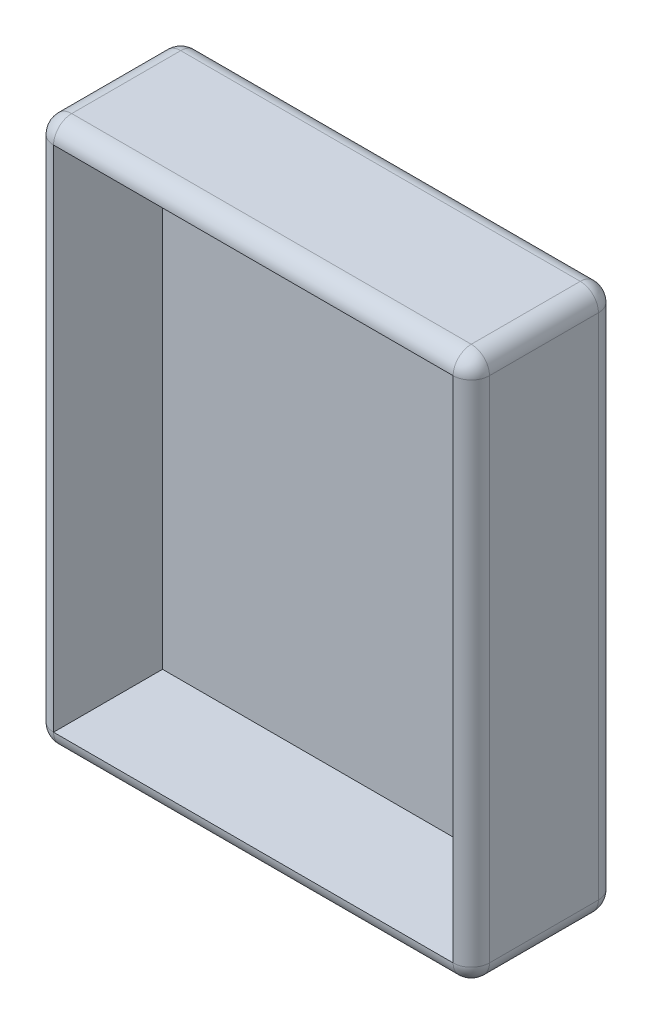
SolidWorks part; units mm, degrees
ref_plane "Front Plane" through (0, 0, 0) normal (0, 0, 1) x (1, 0, 0)
ref_plane "Top Plane" through (0, 0, 0) normal (0, 1, 0) x (1, 0, 0)
ref_plane "Right Plane" through (0, 0, 0) normal (1, 0, 0) x (0, 0, -1)
sketch "Sketch1" plane through (0, 0, 0) normal (0, 0, 1) x (1, 0, 0)
  line L1 (-87.9296, 121.1643) -> (32.0704, 121.1643)
  line L2 (-87.9296, 121.1643) -> (-87.9296, -28.8357)
  line L3 (-87.9296, -28.8357) -> (32.0704, -28.8357)
  line L4 (32.0704, 121.1643) -> (32.0704, -28.8357)
  line L5 (-87.9296, 121.1643) -> (32.0704, -28.8357) construction
  line L6 (-87.9296, -28.8357) -> (32.0704, 121.1643) construction
  point P0 (-27.9296, 46.1643)
extrude "Boss-Extrude1" add sketch "Sketch1" along normal blind 40
fillet "Fillet2" radius 5 12 edges at (-27.9296, -28.8357, 40) (-87.9296, 46.1643, 40) (-27.9296, 121.1643, 40) (32.0704, 46.1643, 40) (-87.9296, -28.8357, 20) (32.0704, -28.8357, 20) (32.0704, 46.1643, 0) (-27.9296, -28.8357, 0) (-87.9296, 46.1643, 0) (-27.9296, 121.1643, 0) (-87.9296, 121.1643, 20) (32.0704, 121.1643, 20)
sketch "Sketch2" plane through (0, 0, 40) normal (0, 0, 1) x (1, 0, 0)
  line L1 (-82.9296, 116.1643) -> (27.0704, 116.1643)
  line L2 (-82.9296, 116.1643) -> (-82.9296, -23.8357)
  line L3 (-82.9296, -23.8357) -> (27.0704, -23.8357)
  line L4 (27.0704, 116.1643) -> (27.0704, -23.8357)
extrude "Cut-Extrude1" cut sketch "Sketch2" against normal blind 30
